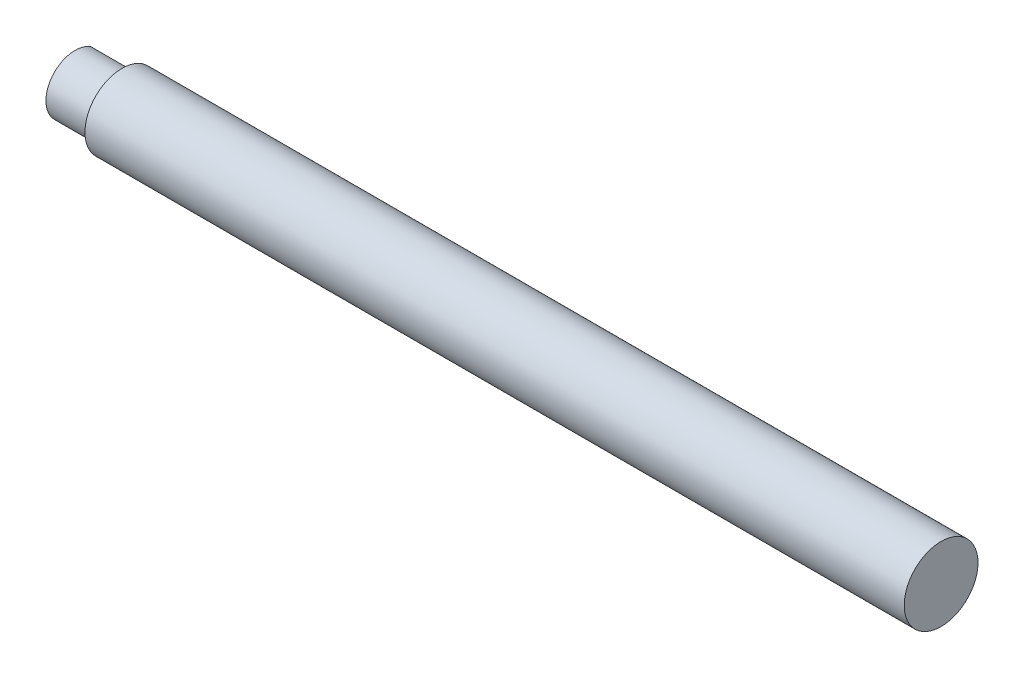
SolidWorks part; units mm, degrees
material "Plain Carbon Steel"
ref_plane "Front Plane" through (0, 0, 0) normal (0, 0, 1) x (1, 0, 0)
ref_plane "Top Plane" through (0, 0, 0) normal (0, 1, 0) x (1, 0, 0)
ref_plane "Right Plane" through (0, 0, 0) normal (1, 0, 0) x (0, 0, -1)
sketch "Sketch1" plane through (0, 0, 0) normal (1, 0, 0) x (0, 0, -1)
  circle A0 centre (0, 0) radius 2.5
  dimension "D1" = 5
extrude "Base" add sketch "Sketch1" along normal blind 58.674
sketch "Sketch2" plane through (0, 0, 0) normal (1, 0, 0) x (0, 0, -1)
  line L0 (1.0795, 1.6461) -> (1.0795, -1.6461)
  arc A0 (1.0795, 1.6461) -> (1.0795, -1.6461) centre (0, 0) ccw
  dimension "D1" = 3.937
  dimension "D2" = 1.0795
extrude "Cut-Extrude1" cut sketch "Sketch2" along normal blind 3.175 flip side to cut
